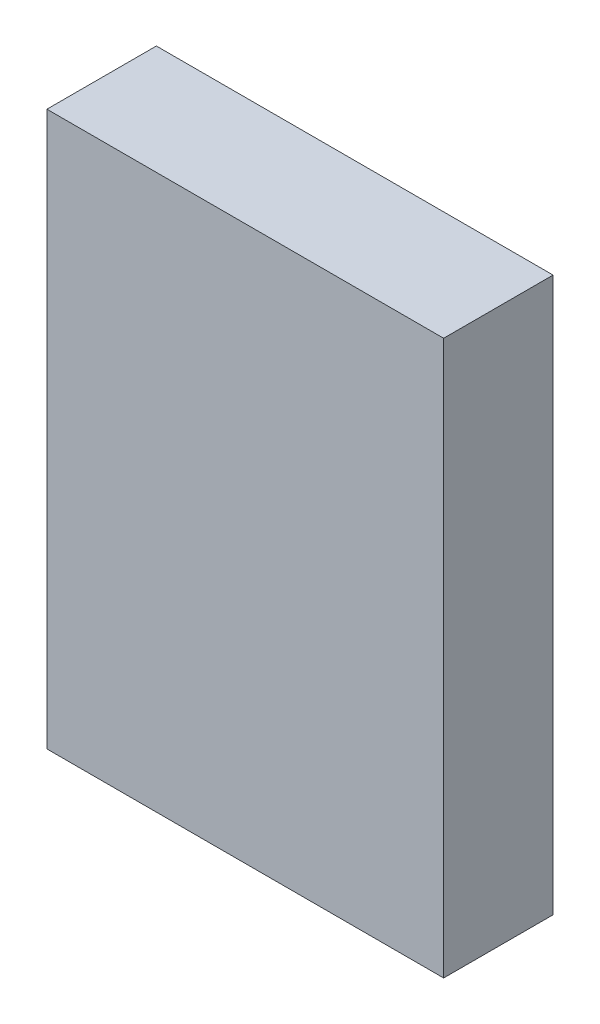
SolidWorks part; units mm, degrees
ref_plane "Front Plane" through (0, 0, 0) normal (0, 0, 1) x (1, 0, 0)
ref_plane "Top Plane" through (0, 0, 0) normal (0, 1, 0) x (1, 0, 0)
ref_plane "Right Plane" through (0, 0, 0) normal (1, 0, 0) x (0, 0, -1)
sketch "Sketch2" plane through (0, 0, 0) normal (0, 0, 1) x (1, 0, 0)
  line L1 (0, 0) -> (184.15, 0)
  line L2 (0, 0) -> (0, 257.175)
  line L3 (0, 257.175) -> (184.15, 257.175)
  line L4 (184.15, 0) -> (184.15, 257.175)
  dimension "D1" = 184.15
  dimension "D2" = 257.175
extrude "Boss-Extrude1" add sketch "Sketch2" along normal blind 50.8
